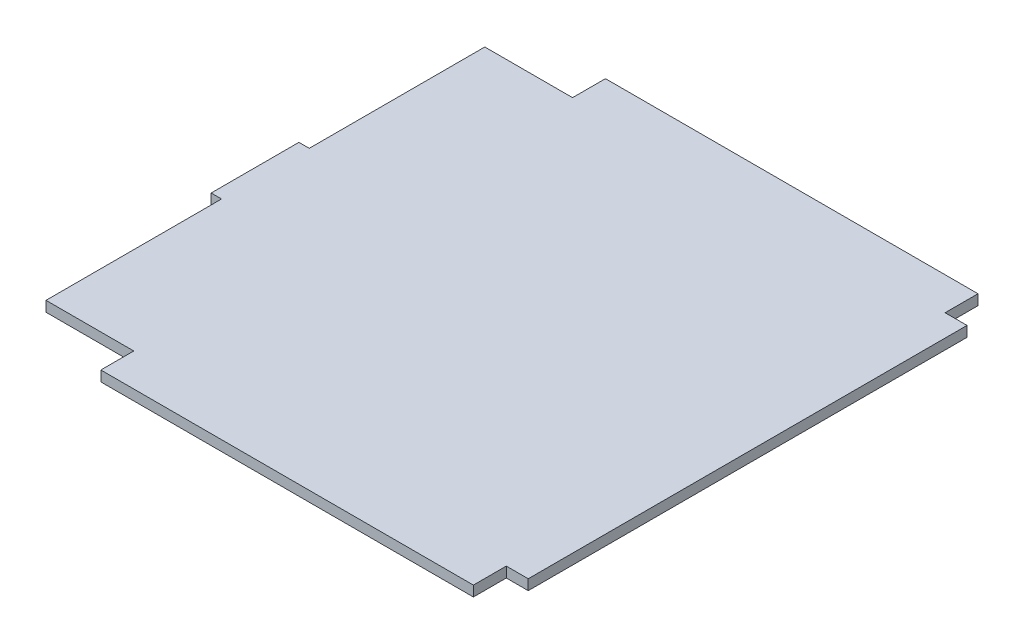
SolidWorks part; units mm, degrees
ref_plane "Front Plane" through (0, 0, 0) normal (0, 0, 1) x (1, 0, 0)
ref_plane "Top Plane" through (0, 0, 0) normal (0, 1, 0) x (1, 0, 0)
ref_plane "Right Plane" through (0, 0, 0) normal (1, 0, 0) x (0, 0, -1)
sketch "Sketch1" plane through (0, 0, 0) normal (0, 1, 0) x (1, 0, 0)
  line L0 (-69.7865, 66.4972) -> (69.7865, 66.4972) construction
  line L1 (69.7865, -73.025) -> (-69.7865, -73.025)
  line L2 (69.7865, -73.025) -> (69.7865, 73.025)
  line L3 (69.7865, 73.025) -> (-69.7865, 73.025)
  line L4 (-69.7865, -73.025) -> (-69.7865, 73.025)
  line L5 (69.7865, -73.025) -> (-69.7865, 73.025) construction
  line L6 (69.7865, 73.025) -> (-69.7865, -73.025) construction
  line L7 (-69.7865, -66.4972) -> (69.7865, -66.4972) construction
  line L8 (-69.7865, 66.4972) -> (-69.7865, -66.4972) construction
  line L9 (69.7865, 66.4972) -> (69.7865, -66.4972) construction
  line L19 (-69.7865, -12.7) -> (-72.7837, -12.7)
  line L20 (-69.7865, -73.025) -> (-44.3865, -73.025)
  line L21 (-69.7865, -73.025) -> (-69.7865, -63.5)
  line L22 (-69.7865, -63.5) -> (-44.3865, -63.5)
  line L23 (-44.3865, -73.025) -> (-44.3865, -63.5)
  line L24 (-69.7865, 73.025) -> (-44.3865, 73.025)
  line L25 (-69.7865, 73.025) -> (-69.7865, 63.5)
  line L26 (-69.7865, 63.5) -> (-44.3865, 63.5)
  line L27 (-44.3865, 73.025) -> (-44.3865, 63.5)
  line L28 (-69.7865, -12.7) -> (-69.7865, 12.7)
  line L29 (-69.7865, 12.7) -> (-72.7837, 12.7)
  line L30 (-72.7837, -12.7) -> (-72.7837, 12.7)
  line L31 (69.7865, 73.025) -> (63.4365, 73.025)
  line L32 (69.7865, 73.025) -> (69.7865, 63.5)
  line L33 (69.7865, 63.5) -> (63.4365, 63.5)
  line L34 (63.4365, 73.025) -> (63.4365, 63.5)
  line L35 (69.7865, -73.025) -> (63.4365, -73.025)
  line L36 (69.7865, -73.025) -> (69.7865, -63.5)
  line L37 (69.7865, -63.5) -> (63.4365, -63.5)
  line L38 (63.4365, -73.025) -> (63.4365, -63.5)
  point P0 (0, 0)
  point P10 (69.7865, 0)
  point P11 (69.7865, 0)
  point P16 (-72.7837, 0)
  dimension "D1" = 139.573
  dimension "D2" = 146.05
  dimension "D3" = 132.9944
  dimension "D4" = 127
  dimension "D5" = 25.4
  dimension "D6" = 25.4
  dimension "D7" = 2.9972
  dimension "D8" = 6.35
extrude "Boss-Extrude1" add sketch "Sketch1" along normal blind 2.9972 contours L3 L27 L26 L4 L22 L23 L1 L2 | L30 L19 L4 L29
